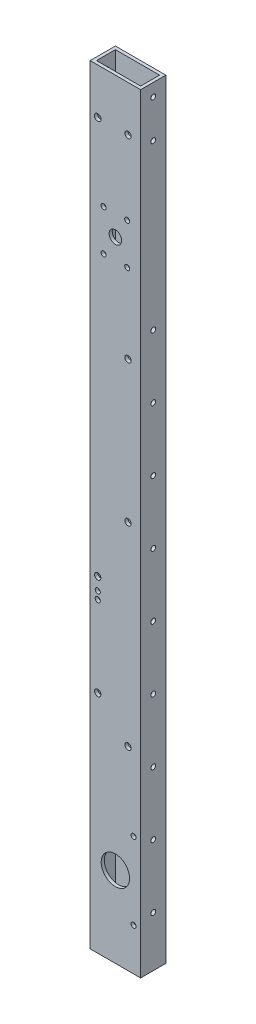
SolidWorks part; units mm, degrees
material "1060 Alloy"
ref_plane "Front Plane" through (0, 0, 0) normal (0, 0, 1) x (1, 0, 0)
ref_plane "Top Plane" through (0, 0, 0) normal (0, 1, 0) x (1, 0, 0)
ref_plane "Right Plane" through (0, 0, 0) normal (1, 0, 0) x (0, 0, -1)
sketch "Sketch1" plane through (0, 0, 0) normal (0, 1, 0) x (1, 0, 0)
  line L0 (-3.175, 22.225) -> (47.625, 22.225)
  line L1 (0, 0) -> (44.45, 0)
  line L2 (0, 0) -> (0, 19.05)
  line L3 (0, 19.05) -> (44.45, 19.05)
  line L4 (44.45, 0) -> (44.45, 19.05)
  line L5 (47.625, -3.175) -> (47.625, 22.225)
  line L6 (-3.175, -3.175) -> (47.625, -3.175)
  line L7 (-3.175, -3.175) -> (-3.175, 22.225)
  dimension "D2" = 25.4
  dimension "D3" = 50.8
  dimension "D1" = 3.175
extrude "Boss-Extrude1" add sketch "Sketch1" along normal blind 774.7
sketch "Sketch3" plane through (0, 0, 3.175) normal (0, 0, 1) x (1, 0, 0)
  line L0 (47.625, 774.7) -> (47.625, 0) construction
  line L1 (-3.175, 0) -> (47.625, 0) construction
  circle A0 centre (22.225, 81.28) radius 14.2875
  dimension "D1" = 28.575
  dimension "D2" = 25.4
  dimension "D3" = 81.28
extrude "Cut-Extrude2" cut sketch "Sketch3" against normal through all
sketch "Sketch2" plane through (0, 0, 3.175) normal (0, 0, 1) x (1, 0, 0)
  line L1 (47.625, 774.7) -> (47.625, 0) construction
  circle A0 centre (22.225, 633.476) radius 6.35
  circle A1 centre (22.225, 81.28) radius 14.2875 construction
  dimension "D1" = 12.7
  dimension "D2" = 552.196
  dimension "D3" = 25.4
extrude "Cut-Extrude1" cut sketch "Sketch2" against normal through all
sketch "Sketch4" plane through (0, 0, 3.175) normal (0, 0, 1) x (1, 0, 0)
  line L0 (-3.175, 81.28) -> (47.625, 81.28) construction
  line L1 (-3.175, 774.7) -> (-3.175, 0) construction
  line L2 (47.625, 774.7) -> (47.625, 0) construction
  line L3 (40.5117, 119.971) -> (40.5117, 81.28) construction
  line L4 (40.5117, 81.28) -> (40.5117, 42.589) construction
  circle A0 centre (40.5117, 42.589) radius 2.54
  circle A1 centre (40.5117, 119.971) radius 2.54
  circle A2 centre (22.225, 81.28) radius 14.2875 construction
  dimension "D3" = 5.08
  dimension "D1" = 38.691
  dimension "D2" = 18.2867
extrude "Cut-Extrude3" cut sketch "Sketch4" against normal through all
sketch "Sketch5" plane through (0, 0, -22.225) normal (0, 0, -1) x (-1, 0, 0)
  line L1 (-10.3188, 612.8538) -> (-34.1312, 612.8538) construction
  line L2 (-10.3188, 612.8538) -> (-10.3188, 654.0982) construction
  line L3 (-10.3188, 654.0982) -> (-34.1312, 654.0982) construction
  line L4 (-34.1312, 612.8538) -> (-34.1312, 654.0982) construction
  line L5 (-10.3188, 612.8538) -> (-34.1312, 654.0982) construction
  line L6 (-10.3188, 654.0982) -> (-34.1312, 612.8538) construction
  circle A4 centre (-10.3188, 612.8538) radius 2.54
  circle A5 centre (-34.1312, 612.8538) radius 2.54
  circle A6 centre (-10.3188, 654.0982) radius 2.54
  circle A7 centre (-34.1312, 654.0982) radius 2.54
  point P1 (-22.225, 633.476)
  dimension "D3" = 5.08
  dimension "D1" = 41.2445
  dimension "D2" = 23.8125
extrude "Cut-Extrude4" cut sketch "Sketch5" against normal through all
sketch "Sketch6" plane through (0, 0, 3.175) normal (0, 0, 1) x (1, 0, 0)
  line L0 (4.445, 227.076) -> (4.445, 328.676) construction
  line L1 (-3.175, 774.7) -> (-3.175, 0) construction
  circle A0 centre (4.445, 227.076) radius 3.175
  circle A1 centre (4.445, 328.676) radius 3.175
  circle A2 centre (22.225, 633.476) radius 6.35 construction
  dimension "D1" = 6.35
  dimension "D2" = 101.6
  dimension "D3" = 7.62
  dimension "D4" = 304.8
extrude "Cut-Extrude5" cut sketch "Sketch6" against normal through all and the other way through all
sketch "Sketch8" plane through (0, 0, 3.175) normal (0, 0, 1) x (1, 0, 0)
  line L0 (4.445, 246.9217) -> (4.445, 385.6377) construction
  circle A0 centre (4.445, 315.976) radius 2.5797
  circle A1 centre (4.445, 308.356) radius 2.5797
  circle A2 centre (4.445, 227.076) radius 3.175 construction
  dimension "D1" = 5.1594
  dimension "D2" = 88.9
  dimension "D3" = 81.28
extrude "Cut-Extrude8" cut sketch "Sketch8" against normal through all
sketch "Sketch10" plane through (0, 0, 3.175) normal (0, 0, 1) x (1, 0, 0)
  line L0 (47.625, 774.7) -> (47.625, 0) construction
  line L1 (13.97, 0) -> (-13.97, 0) construction
  circle A0 centre (34.925, 195.58) radius 3.175
  circle A1 centre (34.925, 391.16) radius 3.175
  circle A2 centre (34.925, 533.4) radius 3.175
  circle A3 centre (34.925, 728.98) radius 3.175
  circle A4 centre (4.445, 728.98) radius 3.3734
  dimension "D1" = 12.7
  dimension "D2" = 6.35
  dimension "D3" = 195.58
  dimension "D4" = 195.58
  dimension "D5" = 142.24
  dimension "D6" = 195.58
  dimension "D7" = 6.7469
  dimension "D8" = 30.48
extrude "Cut-Extrude9" cut sketch "Sketch10" against normal through all
sketch "Sketch11" plane through (-3.175, 0, 0) normal (-1, 0, 0) x (0, 0, 1)
  line L0 (-22.225, 0) -> (3.175, 0) construction
  line L1 (3.175, 774.7) -> (3.175, 0) construction
  line L2 (-22.225, 774.7) -> (3.175, 774.7) construction
  circle A0 centre (-9.525, 762) radius 2.4638
  circle A1 centre (-9.525, 723.9) radius 2.4638
  circle A2 centre (-9.525, 558.8) radius 2.4638
  circle A3 centre (-9.525, 533.4) radius 2.4638
  circle A4 centre (-9.525, 495.3) radius 2.4638
  circle A5 centre (-9.525, 50.8) radius 2.4638
  circle A6 centre (-9.525, 12.7) radius 2.4638
  point P16 (-9.525, 0)
  dimension "D1" = 4.9276
  dimension "D2" = 4.9276
  dimension "D3" = 4.9276
  dimension "D5" = 25.4
  dimension "D6" = 558.8
  dimension "D8" = 4.9276
  dimension "D9" = 4.9276
  dimension "D10" = 38.1
  dimension "D12" = 12.7
  dimension "D13" = 12.7
  dimension "D4" = 38.1
  dimension "D7" = 12.7
  dimension "D11" = 50.8
extrude "Cut-Extrude10" cut sketch "Sketch11" against normal up to next
sketch "Sketch12" plane through (47.625, 0, 0) normal (1, 0, 0) x (0, 0, -1)
  circle A0 centre (9.525, 50.8) radius 2.4638
  circle A1 centre (9.525, 114.3) radius 2.4638
  circle A2 centre (9.525, 177.8) radius 2.4638
  circle A3 centre (9.525, 241.3) radius 2.4638
  circle A4 centre (9.525, 304.8) radius 2.4638
  circle A5 centre (9.525, 368.3) radius 2.4638
  circle A6 centre (9.525, 431.8) radius 2.4638
  circle A7 centre (9.525, 495.3) radius 2.4638
  circle A8 centre (9.525, 558.8) radius 2.4638
extrude "Cut-Extrude11" cut sketch "Sketch12" against normal up to next
sketch "Sketch13" plane through (47.625, 0, 0) normal (1, 0, 0) x (0, 0, -1)
  line L0 (22.225, 774.7) -> (22.225, 0) construction
  line L1 (-3.175, 774.7) -> (22.225, 774.7) construction
  circle A0 centre (9.525, 762) radius 2.4638
  circle A1 centre (9.525, 723.9) radius 2.4638
  dimension "D1" = 38.1
  dimension "D2" = 12.7
  dimension "D3" = 50.8
  dimension "D4" = 4.9276
extrude "Cut-Extrude12" cut sketch "Sketch13" against normal up to next
